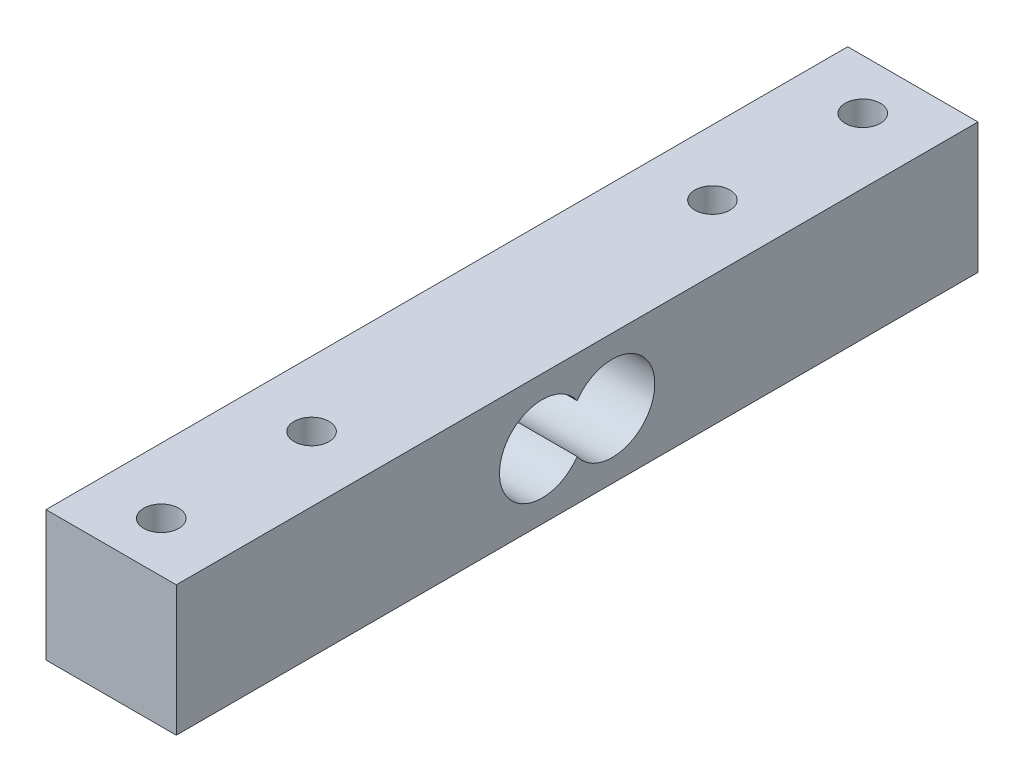
SolidWorks part; units mm, degrees
ref_plane "정면" through (0, 0, 0) normal (0, 0, 1) x (1, 0, 0)
ref_plane "윗면" through (0, 0, 0) normal (0, 1, 0) x (1, 0, 0)
ref_plane "우측면" through (0, 0, 0) normal (1, 0, 0) x (0, 0, -1)
sketch "스케치1" plane through (0, 0, 0) normal (0, 1, 0) x (1, 0, 0)
  line L1 (-6.5, -40) -> (6.5, -40)
  line L2 (-6.5, -40) -> (-6.5, 40)
  line L3 (-6.5, 40) -> (6.5, 40)
  line L4 (6.5, -40) -> (6.5, 40)
  line L5 (-6.5, -40) -> (6.5, 40) construction
  line L6 (-6.5, 40) -> (6.5, -40) construction
  point P0 (0, 0)
  dimension "D1" = 80
  dimension "D2" = 13
extrude "보스-돌출1" add sketch "스케치1" along normal mid plane 13
sketch "스케치3" plane through (0, 0, 0) normal (1, 0, 0) x (0, 0, -1)
  line L0 (-7.75, 0) -> (7.75, 0) construction
  circle A0 centre (3.5, 0) radius 4.25
  circle A1 centre (-3.5, 0) radius 4.25
  point P4 (0, 0)
  dimension "D2" = 8.5
  dimension "D1" = 15.5
extrude "컷-돌출1" cut sketch "스케치3" against normal through all both and the other way through all contours A1 L0 A0 | A1 L0 A0 | L0 A1 A0 | L0 A1 A0 | L0 A0 A1 | A0 L0 A1
sketch "스케치4" plane through (0, 0, 0) normal (0, 1, 0) x (1, 0, 0)
  line L0 (0, 40) -> (0, 35) construction
  line L1 (6.5, 40) -> (-6.5, 40) construction
  line L2 (0, 35) -> (0, 20) construction
  circle A0 centre (0, 35) radius 1.75
  circle A1 centre (0, 20) radius 1.75
  dimension "D1" = 3.5
  dimension "D2" = 15
  dimension "D3" = 5
extrude "컷-돌출2" cut sketch "스케치4" against normal through all both and the other way through all
mirror "대칭 복사1" about plane through (0, 0, 0) normal (0, 0, 1) of "컷-돌출2"
